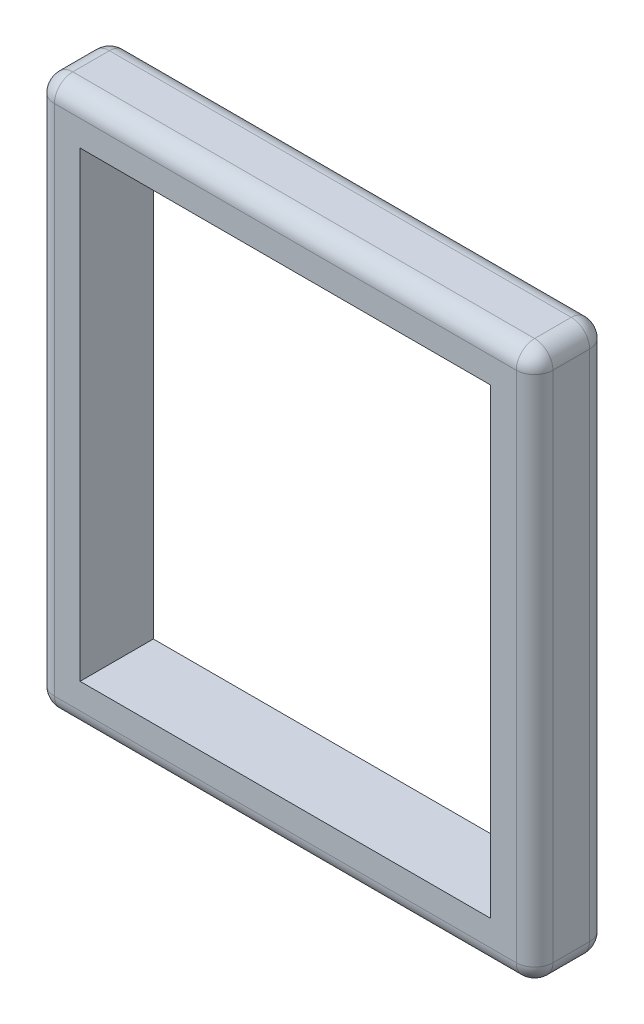
SolidWorks part; units mm, degrees
ref_plane "Front" through (0, 0, 0) normal (0, 0, 1) x (1, 0, 0)
ref_plane "Top" through (0, 0, 0) normal (0, 1, 0) x (1, 0, 0)
ref_plane "Right" through (0, 0, 0) normal (1, 0, 0) x (0, 0, -1)
sketch "Sketch1" plane through (0, 0, 0) normal (0, 0, 1) x (1, 0, 0)
  line L1 (0, 0) -> (-86.36, 0)
  line L2 (0, 0) -> (0, 95.25)
  line L3 (0, 95.25) -> (-86.36, 95.25)
  line L4 (-86.36, 0) -> (-86.36, 95.25)
  line L5 (-78.74, 87.63) -> (-7.62, 87.63)
  line L6 (-78.74, 87.63) -> (-78.74, 7.62)
  line L7 (-78.74, 7.62) -> (-7.62, 7.62)
  line L8 (-7.62, 87.63) -> (-7.62, 7.62)
  dimension "D1" = 7.62
  dimension "D2" = 7.62
  dimension "D3" = 7.62
  dimension "D4" = 7.62
  dimension "D5" = 71.12
  dimension "D6" = 80.01
extrude "Boss-Extrude1" add sketch "Sketch1" along normal blind 12.7
fillet "Fillet1" radius 3.175 12 edges at (-86.36, 47.625, 12.7) (-86.36, 47.625, 0) (-43.18, 95.25, 12.7) (-86.36, 95.25, 6.35) (-43.18, 95.25, 0) (0, 47.625, 12.7) (0, 95.25, 6.35) (0, 47.625, 0) (-86.36, 0, 6.35) (-43.18, 0, 12.7) (0, 0, 6.35) (-43.18, 0, 0)
equation "\"D2@Sketch1\"=\"D1@Sketch1\""
equation "\"D3@Sketch1\"=\"D1@Sketch1\""
equation "\"D4@Sketch1\"=\"D1@Sketch1\""
